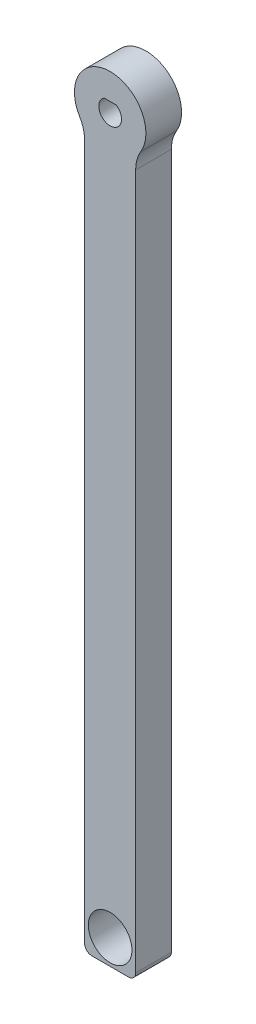
SolidWorks part; units mm, degrees
ref_plane "Front Plane" through (0, 0, 0) normal (0, 0, 1) x (1, 0, 0)
ref_plane "Top Plane" through (0, 0, 0) normal (0, 1, 0) x (1, 0, 0)
ref_plane "Right Plane" through (0, 0, 0) normal (1, 0, 0) x (0, 0, -1)
sketch "Sketch1" plane through (0, 0, 0) normal (0, 0, 1) x (1, 0, 0)
  line L0 (-1.6093, 2.52) -> (1.6093, 2.52)
  line L1 (-1.6666, 2.72) -> (1.6666, 2.72)
  arc A0 (-1.6186, 2.514) -> (1.6093, 2.52) centre (0, 0) ccw
  arc A1 (-1.6666, 2.72) -> (1.6666, 2.72) centre (0, 0) ccw
  circle A2 centre (0, 0) radius 10
  arc A3 (-1.6093, 2.52) -> (1.6093, 2.52) centre (0, 0) ccw construction
  dimension "D1" = 5.98
  dimension "D4" = 20
  dimension "D2" = 2.52
  dimension "D3" = 0.2
extrude "Boss-Extrude1" add sketch "Sketch1" along normal blind 10 contours A2 A1 L1
sketch "Sketch2" plane through (0, 0, 0) normal (0, 0, -1) x (-1, 0, 0)
  line L5 (-10, -7) -> (10, -7)
  line L6 (-10, -7) -> (-10, -10)
  line L7 (-10, -10) -> (10, -10)
  line L8 (10, -7) -> (10, -10)
  circle A1 centre (0, 0) radius 10
  circle A2 centre (0, 0) radius 10
  circle M8 centre (0, 0) radius 10
  dimension "D2" = 3
  dimension "D1" = 0
extrude "Cut-Extrude1" cut sketch "Sketch2" against normal blind 10 contours L5 M8
sketch "Sketch3" plane through (0, -7, 0) normal (0, -1, 0) x (1, 0, 0)
  line L4 (-7.1414, 0) -> (7.1414, 0)
  line L5 (7.1414, 0) -> (7.1414, 10)
  line L6 (7.1414, 10) -> (-7.1414, 10)
  line L7 (-7.1414, 10) -> (-7.1414, 0)
  line L8 (-7.1414, 0) -> (7.1414, 0)
  line L9 (7.1414, 0) -> (7.1414, 10)
  line L10 (7.1414, 10) -> (-7.1414, 10)
  line L11 (-7.1414, 10) -> (-7.1414, 0)
  dimension "D1" = 0
extrude "Boss-Extrude2" add sketch "Sketch3" along normal blind 200
sketch "Sketch4" plane through (0, 0, 0) normal (0, 0, -1) x (-1, 0, 0)
  line L0 (7.1414, -207) -> (-7.1414, -207) construction
  circle A0 centre (0, -200) radius 6.11
  dimension "D1" = 12.22
  dimension "D2" = 7
extrude "Cut-Extrude2" cut sketch "Sketch4" against normal blind 10
fillet "Fillet1" radius 10 2 edges at (-7.1414, -7, 5) (7.1414, -7, 5)
fillet "Fillet2" radius 2 2 edges at (7.1414, -207, 5) (-7.1414, -207, 5)
